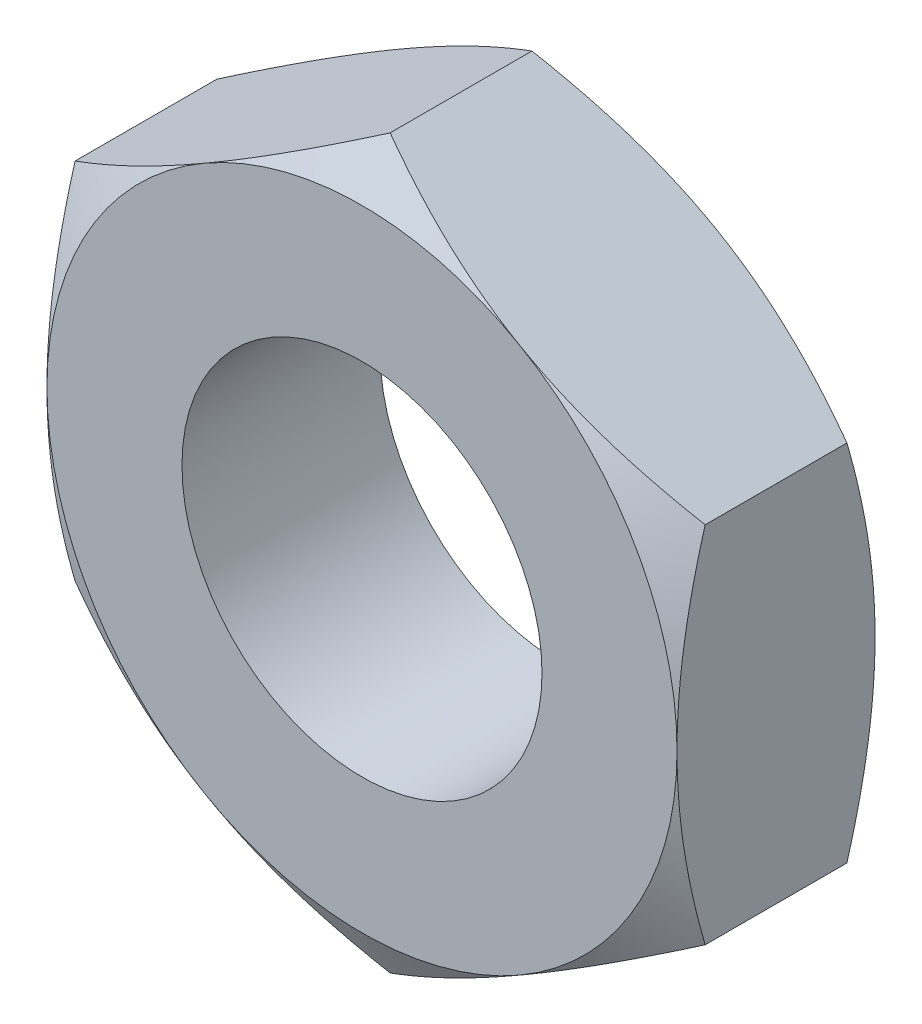
SolidWorks part; units mm, degrees
material "1.4000 (X6Cr13)"
ref_plane "Płaszczyzna przednia" through (0, 0, 0) normal (0, 0, 1) x (1, 0, 0)
ref_plane "Płaszczyzna górna" through (0, 0, 0) normal (0, 1, 0) x (1, 0, 0)
ref_plane "Płaszczyzna prawa" through (0, 0, 0) normal (1, 0, 0) x (0, 0, -1)
sketch "Szkic1" plane through (0, 0, 0) normal (0, 0, 1) x (1, 0, 0)
  line L1 (-3.5, 2.0207) -> (-3.5, -2.0207)
  line L2 (-3.5, -2.0207) -> (0, -4.0415)
  line L3 (0, -4.0415) -> (3.5, -2.0207)
  line L4 (3.5, -2.0207) -> (3.5, 2.0207)
  line L5 (3.5, 2.0207) -> (0, 4.0415)
  line L6 (0, 4.0415) -> (-3.5, 2.0207)
  circle A0 centre (0, 0) radius 2
  circle A1 centre (0, 0) radius 3.5 construction
  dimension "d" = 4
  dimension "s" = 7
extrude "Dodanie-wyciągnięcie1" add sketch "Szkic1" along normal mid plane 2.2
sketch "Szkic2" plane through (0, 0, 1.1) normal (0, 0, 1) x (1, 0, 0)
  circle A0 centre (0, 0) radius 3.5
  dimension "D1" = 7
extrude "Wytnij-wyciągnięcie2" cut sketch "Szkic2" against normal blind 2.2 draft 60 flip side to cut
mirror "Lustro1" about plane through (0, 0, 0) normal (0, 0, 1) of "Wytnij-wyciągnięcie2"
equation "\"D1@Szkic2\" = \"s@Szkic1\""
equation "\"D1@Wytnij-wyciągnięcie2\" = \"m@Dodanie-wyciągnięcie1\""
